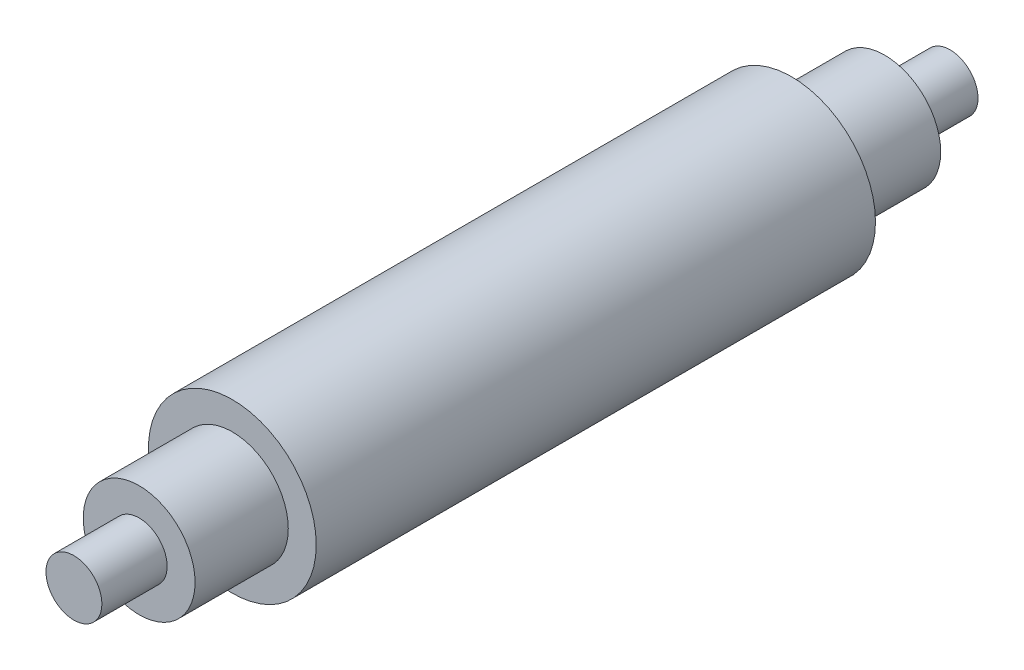
SolidWorks part; units mm, degrees
ref_plane "Front Plane" through (0, 0, 0) normal (0, 0, 1) x (1, 0, 0)
ref_plane "Top Plane" through (0, 0, 0) normal (0, 1, 0) x (1, 0, 0)
ref_plane "Right Plane" through (0, 0, 0) normal (1, 0, 0) x (0, 0, -1)
sketch "Sketch1" plane through (0, 0, 0) normal (0, 0, 1) x (1, 0, 0)
  circle A0 centre (0, 0) radius 45
  dimension "D1" = 90
extrude "Boss-Extrude1" add sketch "Sketch1" against normal mid plane 300
sketch "Sketch2" plane through (0, 0, 150) normal (0, 0, 1) x (1, 0, 0)
  circle A0 centre (0, 0) radius 30
  dimension "D1" = 60
extrude "Boss-Extrude2" add sketch "Sketch2" along normal blind 50
sketch "Sketch3" plane through (0, 0, 200) normal (0, 0, 1) x (1, 0, 0)
  circle A0 centre (0, 0) radius 15
  dimension "D1" = 30
extrude "Boss-Extrude3" add sketch "Sketch3" along normal blind 35
mirror "Mirror2" about plane through (0, 0, 0) normal (0, 0, 1) of "Boss-Extrude3", "Boss-Extrude2"
